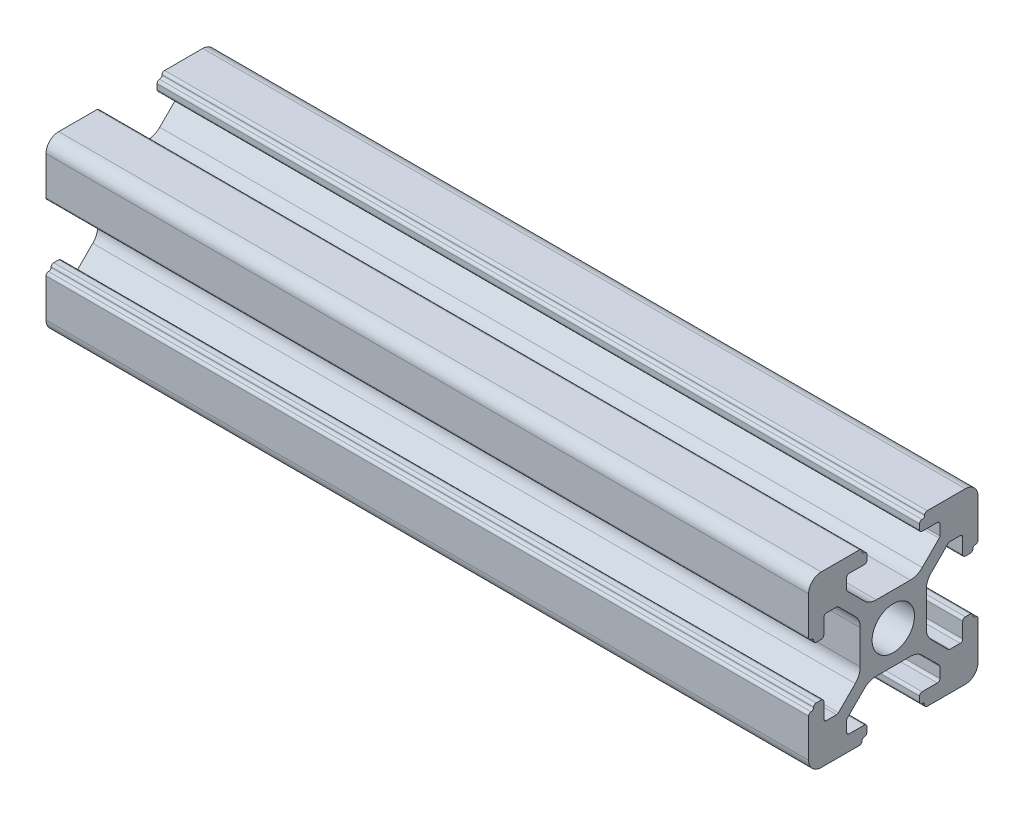
SolidWorks part; units mm, degrees
ref_plane "前视基准面" through (0, 0, 0) normal (0, 0, 1) x (1, 0, 0)
ref_plane "上视基准面" through (0, 0, 0) normal (0, 1, 0) x (1, 0, 0)
ref_plane "右视基准面" through (0, 0, 0) normal (1, 0, 0) x (0, 0, -1)
other "Configuration Table"
sketch "草图1" plane through (0, 0, 0) normal (1, 0, 0) x (0, 0, -1)
  line L0 (-2.5, 0) -> (2.5, 0) construction
  line L1 (10, 8.5) -> (10, 4)
  line L2 (0, 2.5) -> (0, -2.5) construction
  line L3 (10, -8.5) -> (10, -4)
  line L4 (9.1, -3.1) -> (8.5, -3.1)
  line L5 (9.1, 3.1) -> (8.5, 3.1)
  line L6 (8.2, 3.4) -> (8.2, 5.2)
  line L7 (7.9, 5.5) -> (6.6849, 5.5)
  line L8 (6.4728, 5.4121) -> (4.4858, 3.4251)
  line L9 (3.9, 2.0109) -> (3.9, -2.0109)
  line L10 (0, 0) -> (10, 10) construction
  line L11 (8.2, -3.4) -> (8.2, -5.2)
  line L12 (7.9, -5.5) -> (6.6849, -5.5)
  line L13 (6.4728, -5.4121) -> (4.4858, -3.4251)
  line L14 (5.4121, 6.4728) -> (3.4251, 4.4858)
  line L15 (5.5, 7.9) -> (5.5, 6.6849)
  line L16 (3.4, 8.2) -> (5.2, 8.2)
  line L17 (3.1, 9.1) -> (3.1, 8.5)
  line L18 (8.5, 10) -> (4, 10)
  line L19 (-5.4121, 6.4728) -> (-3.4251, 4.4858)
  line L20 (-5.5, 7.9) -> (-5.5, 6.6849)
  line L21 (-3.4, 8.2) -> (-5.2, 8.2)
  line L22 (2.0109, 3.9) -> (-2.0109, 3.9)
  line L23 (-3.1, 9.1) -> (-3.1, 8.5)
  line L24 (-8.5, 10) -> (-4, 10)
  line L25 (-10, 10) -> (0, 0) construction
  line L26 (-10, 8.5) -> (-10, 4)
  line L27 (-9.1, 3.1) -> (-8.5, 3.1)
  line L28 (-3.9, -2.0109) -> (-3.9, 2.0109)
  line L29 (-8.2, 3.4) -> (-8.2, 5.2)
  line L30 (-7.9, 5.5) -> (-6.6849, 5.5)
  line L31 (-6.4728, 5.4121) -> (-4.4858, 3.4251)
  line L32 (-10, -8.5) -> (-10, -4)
  line L33 (-9.1, -3.1) -> (-8.5, -3.1)
  line L34 (-8.2, -3.4) -> (-8.2, -5.2)
  line L35 (-7.9, -5.5) -> (-6.6849, -5.5)
  line L36 (-6.4728, -5.4121) -> (-4.4858, -3.4251)
  line L37 (5.4121, -6.4728) -> (3.4251, -4.4858)
  line L38 (5.5, -7.9) -> (5.5, -6.6849)
  line L39 (3.4, -8.2) -> (5.2, -8.2)
  line L40 (-2.0109, -3.9) -> (2.0109, -3.9)
  line L41 (-5.4121, -6.4728) -> (-3.4251, -4.4858)
  line L42 (-5.5, -7.9) -> (-5.5, -6.6849)
  line L43 (-3.4, -8.2) -> (-5.2, -8.2)
  line L44 (-3.1, -9.1) -> (-3.1, -8.5)
  line L45 (3.1, -9.1) -> (3.1, -8.5)
  line L46 (8.5, -10) -> (4, -10)
  line L47 (-8.5, -10) -> (-4, -10)
  circle A0 centre (0, 0) radius 2.5
  arc A1 (4.4858, 3.4251) -> (3.9, 2.0109) centre (5.9, 2.0109) ccw
  arc A2 (10, 4) -> (9.7, 3.7) centre (9.7, 4) cw
  arc A3 (9.1, 3.1) -> (9.4, 3.4) centre (9.1, 3.4) ccw
  arc A4 (8.5, 3.1) -> (8.2, 3.4) centre (8.5, 3.4) cw
  arc A5 (8.2, 5.2) -> (7.9, 5.5) centre (7.9, 5.2) ccw
  arc A6 (6.6849, 5.5) -> (6.4728, 5.4121) centre (6.6849, 5.2) ccw
  arc A7 (9.4, 3.4) -> (9.7, 3.7) centre (9.7, 3.4) cw
  arc A8 (10, -4) -> (9.7, -3.7) centre (9.7, -4) ccw
  arc A9 (9.4, -3.4) -> (9.7, -3.7) centre (9.7, -3.4) ccw
  arc A10 (9.1, -3.1) -> (9.4, -3.4) centre (9.1, -3.4) cw
  arc A11 (8.5, -3.1) -> (8.2, -3.4) centre (8.5, -3.4) ccw
  arc A12 (8.2, -5.2) -> (7.9, -5.5) centre (7.9, -5.2) cw
  arc A13 (6.6849, -5.5) -> (6.4728, -5.4121) centre (6.6849, -5.2) cw
  arc A14 (4.4858, -3.4251) -> (3.9, -2.0109) centre (5.9, -2.0109) cw
  arc A15 (3.4, 9.4) -> (3.7, 9.7) centre (3.4, 9.7) ccw
  arc A16 (5.5, 6.6849) -> (5.4121, 6.4728) centre (5.2, 6.6849) cw
  arc A17 (5.2, 8.2) -> (5.5, 7.9) centre (5.2, 7.9) cw
  arc A18 (3.1, 8.5) -> (3.4, 8.2) centre (3.4, 8.5) ccw
  arc A19 (3.1, 9.1) -> (3.4, 9.4) centre (3.4, 9.1) cw
  arc A20 (4, 10) -> (3.7, 9.7) centre (4, 9.7) ccw
  arc A21 (-3.4251, 4.4858) -> (-2.0109, 3.9) centre (-2.0109, 5.9) ccw
  arc A22 (-5.5, 6.6849) -> (-5.4121, 6.4728) centre (-5.2, 6.6849) ccw
  arc A23 (-5.2, 8.2) -> (-5.5, 7.9) centre (-5.2, 7.9) ccw
  arc A24 (-3.1, 8.5) -> (-3.4, 8.2) centre (-3.4, 8.5) cw
  arc A25 (-3.1, 9.1) -> (-3.4, 9.4) centre (-3.4, 9.1) ccw
  arc A26 (-3.4, 9.4) -> (-3.7, 9.7) centre (-3.4, 9.7) cw
  arc A27 (-4, 10) -> (-3.7, 9.7) centre (-4, 9.7) cw
  arc A28 (3.4251, 4.4858) -> (2.0109, 3.9) centre (2.0109, 5.9) cw
  arc A29 (-4.4858, -3.4251) -> (-3.9, -2.0109) centre (-5.9, -2.0109) ccw
  arc A30 (-10, 4) -> (-9.7, 3.7) centre (-9.7, 4) ccw
  arc A31 (-9.4, 3.4) -> (-9.7, 3.7) centre (-9.7, 3.4) ccw
  arc A32 (-9.1, 3.1) -> (-9.4, 3.4) centre (-9.1, 3.4) cw
  arc A33 (-8.5, 3.1) -> (-8.2, 3.4) centre (-8.5, 3.4) ccw
  arc A34 (-8.2, 5.2) -> (-7.9, 5.5) centre (-7.9, 5.2) cw
  arc A35 (-6.6849, 5.5) -> (-6.4728, 5.4121) centre (-6.6849, 5.2) cw
  arc A36 (-4.4858, 3.4251) -> (-3.9, 2.0109) centre (-5.9, 2.0109) cw
  arc A37 (-10, -4) -> (-9.7, -3.7) centre (-9.7, -4) cw
  arc A38 (-9.1, -3.1) -> (-9.4, -3.4) centre (-9.1, -3.4) ccw
  arc A39 (-8.5, -3.1) -> (-8.2, -3.4) centre (-8.5, -3.4) cw
  arc A40 (-8.2, -5.2) -> (-7.9, -5.5) centre (-7.9, -5.2) ccw
  arc A41 (-6.6849, -5.5) -> (-6.4728, -5.4121) centre (-6.6849, -5.2) ccw
  arc A42 (-9.4, -3.4) -> (-9.7, -3.7) centre (-9.7, -3.4) cw
  arc A43 (3.4251, -4.4858) -> (2.0109, -3.9) centre (2.0109, -5.9) ccw
  arc A44 (5.5, -6.6849) -> (5.4121, -6.4728) centre (5.2, -6.6849) ccw
  arc A45 (5.2, -8.2) -> (5.5, -7.9) centre (5.2, -7.9) ccw
  arc A46 (3.1, -8.5) -> (3.4, -8.2) centre (3.4, -8.5) cw
  arc A47 (3.1, -9.1) -> (3.4, -9.4) centre (3.4, -9.1) ccw
  arc A48 (3.4, -9.4) -> (3.7, -9.7) centre (3.4, -9.7) cw
  arc A49 (4, -10) -> (3.7, -9.7) centre (4, -9.7) cw
  arc A50 (-3.4, -9.4) -> (-3.7, -9.7) centre (-3.4, -9.7) ccw
  arc A51 (-5.5, -6.6849) -> (-5.4121, -6.4728) centre (-5.2, -6.6849) cw
  arc A52 (-5.2, -8.2) -> (-5.5, -7.9) centre (-5.2, -7.9) cw
  arc A53 (-3.1, -8.5) -> (-3.4, -8.2) centre (-3.4, -8.5) ccw
  arc A54 (-3.1, -9.1) -> (-3.4, -9.4) centre (-3.4, -9.1) cw
  arc A55 (-4, -10) -> (-3.7, -9.7) centre (-4, -9.7) ccw
  arc A56 (-3.4251, -4.4858) -> (-2.0109, -3.9) centre (-2.0109, -5.9) cw
  arc A57 (-10, -8.5) -> (-8.5, -10) centre (-8.5, -8.5) ccw
  arc A58 (8.5, -10) -> (10, -8.5) centre (8.5, -8.5) ccw
  arc A59 (10, 8.5) -> (8.5, 10) centre (8.5, 8.5) ccw
  arc A60 (-10, 8.5) -> (-8.5, 10) centre (-8.5, 8.5) cw
  point P47 (3.9, 0)
  point P86 (0, 3.9)
  point P164 (-3.9, 0)
  point P165 (0, -3.9)
  dimension "D1" = 5
extrude "凸台-拉伸1" add sketch "草图1" along normal blind 90
